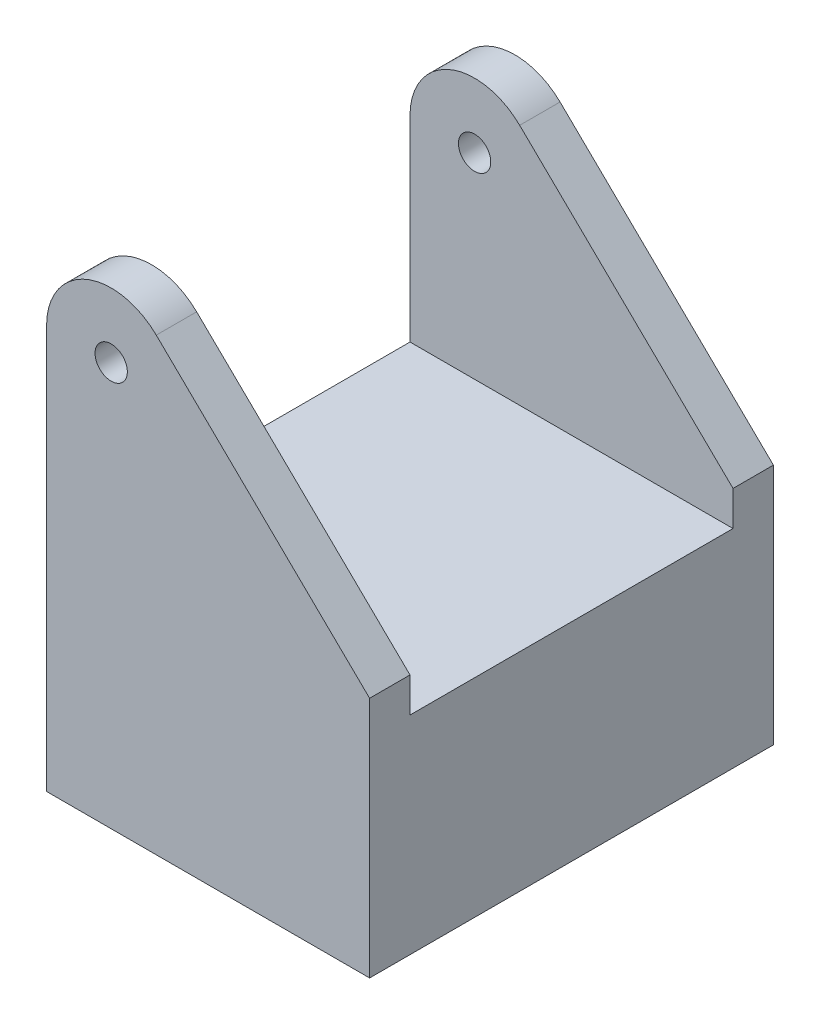
SolidWorks part; units mm, degrees
ref_plane "Alzado" through (0, 0, 0) normal (0, 0, 1) x (1, 0, 0)
ref_plane "Planta" through (0, 0, 0) normal (0, 1, 0) x (1, 0, 0)
ref_plane "Vista lateral" through (0, 0, 0) normal (1, 0, 0) x (0, 0, -1)
sketch "Croquis1" plane through (0, 0, 0) normal (0, 0, 1) x (1, 0, 0)
  line L0 (0, 150) -> (0, 250)
  line L1 (0, 0) -> (200, 0)
  line L2 (0, 0) -> (0, 150)
  line L4 (200, 0) -> (200, 150)
  line L6 (200, 150) -> (67.9091, 278.6545)
  arc A0 (67.9091, 278.6545) -> (0, 250) centre (40, 250) ccw
  circle A1 centre (40, 250) radius 10
  dimension "D3" = 80
  dimension "D1" = 200
  dimension "D2" = 150
extrude "Saliente-Extruir1" add sketch "Croquis1" along normal blind 250
sketch "Croquis3" plane through (0, 0, 0) normal (-1, 0, 0) x (0, 0, 1)
  line L0 (250, 290) -> (0, 290) construction
  line L1 (25, 290) -> (225, 290)
  line L2 (25, 290) -> (25, 128.5)
  line L3 (25, 128.5) -> (225, 128.5)
  line L4 (225, 290) -> (225, 128.5)
  line L5 (250, 250) -> (250, 290) construction
  line L6 (0, 290) -> (0, 250) construction
  point P6 (250, 270)
  dimension "D1" = 25
  dimension "D2" = 25
  dimension "D3" = 161.5
extrude "Cortar-Extruir1" cut sketch "Croquis3" against normal blind 250
